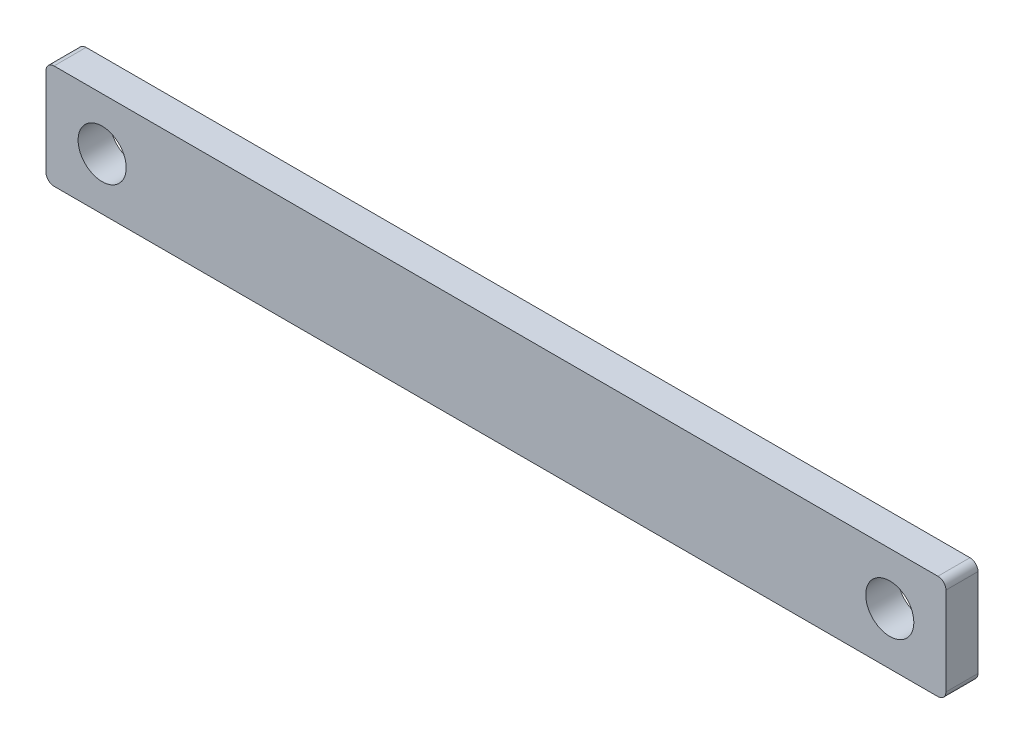
SolidWorks part; units mm, degrees
material "AISI 1020"
ref_plane "Ön Düzlem" through (0, 0, 0) normal (0, 0, 1) x (1, 0, 0)
ref_plane "Üst Düzlem" through (0, 0, 0) normal (0, 1, 0) x (1, 0, 0)
ref_plane "Sağ Düzlem" through (0, 0, 0) normal (1, 0, 0) x (0, 0, -1)
sketch "Çizim1" plane through (0, 0, 0) normal (0, 0, 1) x (1, 0, 0)
  line L1 (10, 0) -> (1112, 0)
  line L2 (0, 10) -> (0, 120)
  line L3 (10, 130) -> (1112, 130)
  line L4 (1122, 10) -> (1122, 120)
  circle A0 centre (70, 65) radius 30
  circle A1 centre (1052, 65) radius 30
  arc A2 (1112, 130) -> (1122, 120) centre (1112, 120) cw
  arc A3 (1112, 0) -> (1122, 10) centre (1112, 10) ccw
  arc A4 (10, 0) -> (0, 10) centre (10, 10) cw
  arc A5 (0, 120) -> (10, 130) centre (10, 120) cw
  point P15 (0, 0)
  point P18 (0, 130)
  dimension "D2" = 60
  dimension "D3" = 60
  dimension "D7" = 10
  dimension "D1" = 130
  dimension "D4" = 70
  dimension "D5" = 70
  dimension "D6" = 982
  dimension "D8" = 65
extrude "Yükseklik-Ekstrüzyon1" add sketch "Çizim1" along normal blind 40
